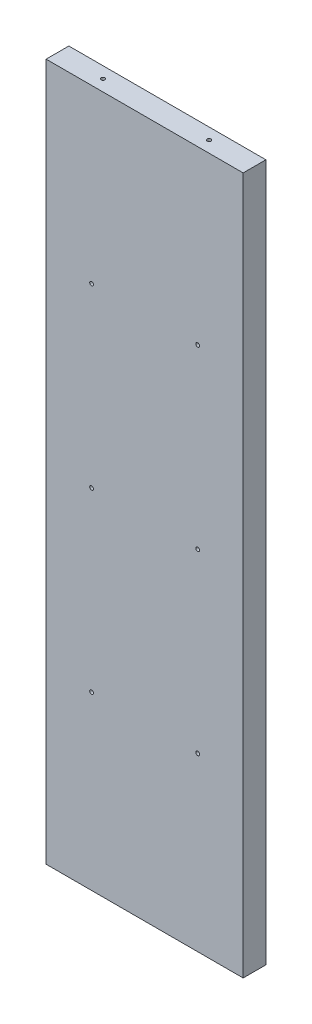
SolidWorks part; units mm, degrees
material "Pin"
ref_plane "Plan de face" through (0, 0, 0) normal (0, 0, 1) x (1, 0, 0)
ref_plane "Plan de dessus" through (0, 0, 0) normal (0, 1, 0) x (1, 0, 0)
ref_plane "Plan de droite" through (0, 0, 0) normal (1, 0, 0) x (0, 0, -1)
sketch "Esquisse1" plane through (0, 0, 0) normal (0, 1, 0) x (1, 0, 0)
  line L1 (-195, -22.5) -> (195, -22.5)
  line L2 (-195, -22.5) -> (-195, 22.5)
  line L3 (-195, 22.5) -> (195, 22.5)
  line L4 (195, -22.5) -> (195, 22.5)
  line L5 (-195, -22.5) -> (195, 22.5) construction
  line L6 (-195, 22.5) -> (195, -22.5) construction
  point P0 (0, 0)
  dimension "D1" = 45
  dimension "D2" = 390
extrude "Boss.-Extru.1" add sketch "Esquisse1" along normal blind 1380
sketch "Esquisse2" plane through (0, 0, 22.5) normal (0, 0, 1) x (1, 0, 0)
  line L0 (0, 1380) -> (0, 0) construction
  line L1 (-195, 1380) -> (195, 1380) construction
  line L2 (-195, 0) -> (195, 0) construction
  line L3 (-195, 1380) -> (-195, 1040) construction
  line L4 (-195, 1380) -> (-195, 0) construction
  line L5 (-195, 1040) -> (-105, 1040) construction
  line L6 (195, 1040) -> (105, 1040) construction
  line L7 (-195, 1380) -> (-195, 690) construction
  line L8 (-195, 690) -> (-105, 690) construction
  line L9 (-195, 1380) -> (-195, 340) construction
  line L10 (-195, 340) -> (-105, 340) construction
  line L11 (195, 340) -> (105, 340) construction
  line L12 (195, 690) -> (105, 690) construction
  circle A0 centre (-105, 1040) radius 3.75
  circle A1 centre (105, 1040) radius 3.75
  circle A2 centre (-105, 690) radius 3.75
  circle A3 centre (-105, 340) radius 3.75
  circle A4 centre (105, 340) radius 3.75
  circle A5 centre (105, 690) radius 3.75
  dimension "D2" = 7.5
  dimension "D4" = 7.5
  dimension "D6" = 7.5
  dimension "D1" = 340
  dimension "D3" = 690
  dimension "D5" = 1040
  dimension "D7" = 90
extrude "Enlèv. mat.-Extru.1" cut sketch "Esquisse2" against normal blind 20
sketch "Esquisse3" plane through (0, 1380, 0) normal (0, 1, 0) x (1, 0, 0)
  line L0 (-195, 0) -> (-105, 0) construction
  line L1 (-195, 22.5) -> (-195, -22.5) construction
  line L2 (195, 0) -> (105, 0) construction
  line L3 (195, -22.5) -> (195, 22.5) construction
  circle A0 centre (-105, 0) radius 3.75
  circle A1 centre (105, 0) radius 3.75
  dimension "D1" = 7.5
  dimension "D2" = 7.5
  dimension "D3" = 90
  dimension "D4" = 90
extrude "Enlèv. mat.-Extru.2" cut sketch "Esquisse3" against normal blind 20
sketch "Esquisse4" plane through (0, 0, 0) normal (0, -1, 0) x (1, 0, 0)
  line L0 (-195, 0) -> (-105, 0) construction
  line L1 (-195, -22.5) -> (-195, 22.5) construction
  line L2 (195, 0) -> (105, 0) construction
  line L3 (195, 22.5) -> (195, -22.5) construction
  circle A0 centre (-105, 0) radius 3.75
  circle A1 centre (105, 0) radius 3.75
  dimension "D3" = 7.5
  dimension "D4" = 7.5
  dimension "D1" = 90
  dimension "D2" = 90
extrude "Enlèv. mat.-Extru.3" cut sketch "Esquisse4" against normal blind 20
